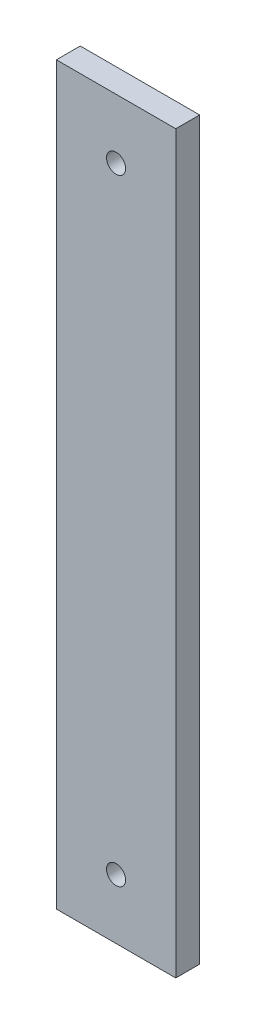
SolidWorks part; units mm, degrees
material "Plain Carbon Steel"
ref_plane "Front Plane" through (0, 0, 0) normal (0, 0, 1) x (1, 0, 0)
ref_plane "Top Plane" through (0, 0, 0) normal (0, 1, 0) x (1, 0, 0)
ref_plane "Right Plane" through (0, 0, 0) normal (1, 0, 0) x (0, 0, -1)
sketch "Sketch1" plane through (0, 0, 0) normal (0, 1, 0) x (1, 0, 0)
  line L1 (-25, -5) -> (25, -5)
  line L2 (-25, -5) -> (-25, 5)
  line L3 (-25, 5) -> (25, 5)
  line L4 (25, -5) -> (25, 5)
  line L5 (-25, -5) -> (25, 5) construction
  line L6 (-25, 5) -> (25, -5) construction
  point P0 (0, 0)
  dimension "D1" = 50
  dimension "D2" = 10
extrude "Boss-Extrude1" add sketch "Sketch1" along normal mid plane 308
sketch "Sketch2" plane through (0, 0, -5) normal (0, 0, -1) x (-1, 0, 0)
  line L0 (0, 0) -> (48.8129, 0) construction
  line L1 (-25, 154) -> (25, 154) construction
  circle A0 centre (0, -129) radius 4
  circle A1 centre (0, 129) radius 4
  point P7 (0, 0)
  point P10 (0, 0)
  dimension "D1" = 8
  dimension "D2" = 258
  dimension "D3" = 25
extrude "Cut-Extrude1" cut sketch "Sketch2" against normal through all
